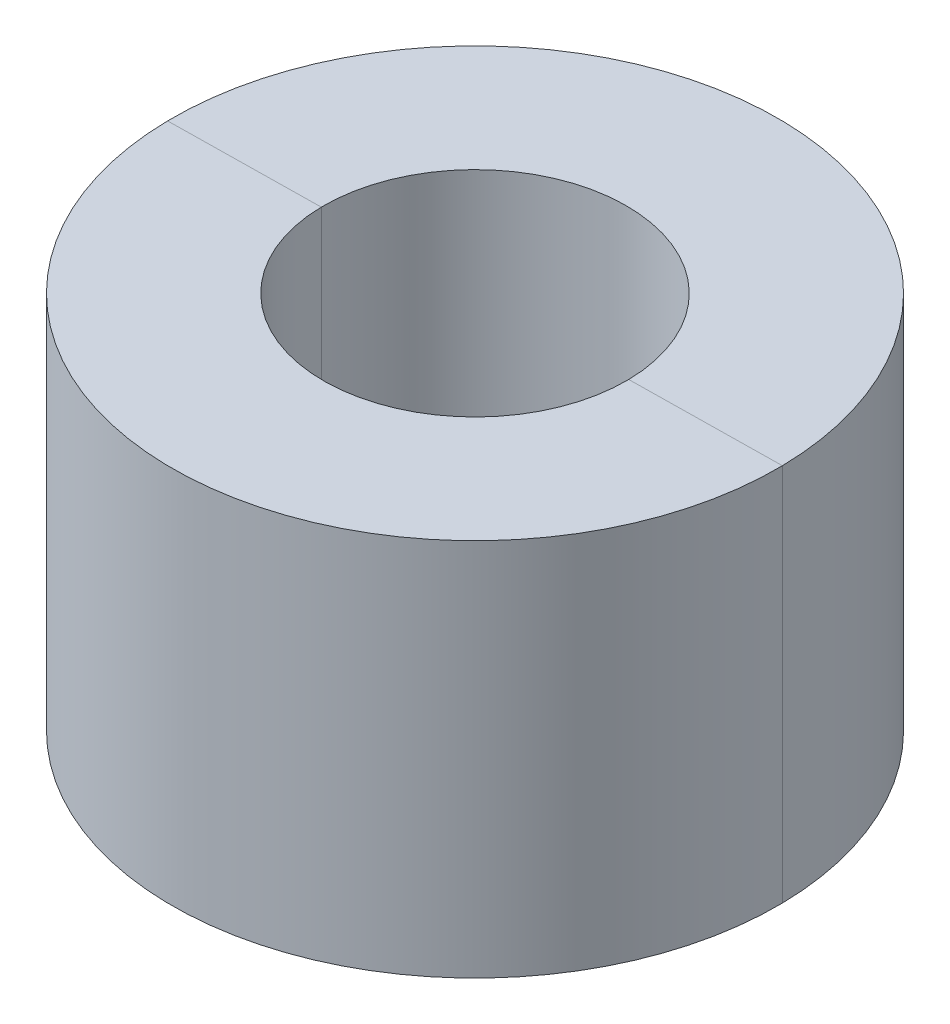
SolidWorks part; units mm, degrees
material "Copper"
ref_plane "Front Plane" through (0, 0, 0) normal (0, 0, 1) x (1, 0, 0)
ref_plane "Top Plane" through (0, 0, 0) normal (0, 1, 0) x (1, 0, 0)
ref_plane "Right Plane" through (0, 0, 0) normal (1, 0, 0) x (0, 0, -1)
sketch "Sketch1" plane through (0, 0, 0) normal (0, 1, 0) x (1, 0, 0)
  circle A0 centre (0, 0) radius 20
  dimension "D1" = 40
extrude "Extrude-Thin1" add sketch "Sketch1" along normal blind 25 thin thin type one direction reverse wall 10
sketch "Sketch2" plane through (0, 25, 0) normal (0, 1, 0) x (1, 0, 0)
  line L0 (-26.5126, -0.3864) -> (28.8296, 0.4202)
split "Split1" trim tools "Sketch2" bodies to split 101 resulting bodies 103 104
